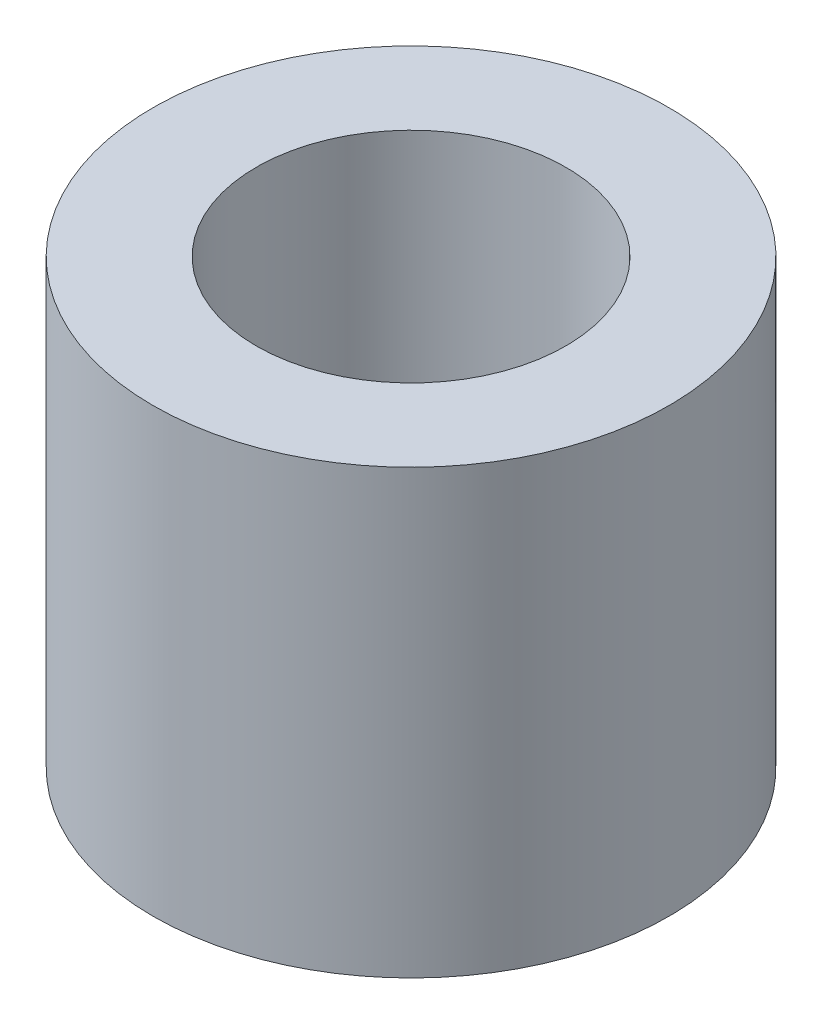
SolidWorks part; units mm, degrees
material "ABS"
ref_plane "前视基准面" through (0, 0, 0) normal (0, 0, 1) x (1, 0, 0)
ref_plane "上视基准面" through (0, 0, 0) normal (0, 1, 0) x (1, 0, 0)
ref_plane "右视基准面" through (0, 0, 0) normal (1, 0, 0) x (0, 0, -1)
sketch "草图1" plane through (0, 0, 0) normal (0, 1, 0) x (1, 0, 0)
  circle A0 centre (0, 0) radius 2.1
  circle A1 centre (0, 0) radius 3.5
  dimension "D1" = 7
  dimension "D2" = 4.2
extrude "凸台-拉伸1" add sketch "草图1" along normal blind 6
